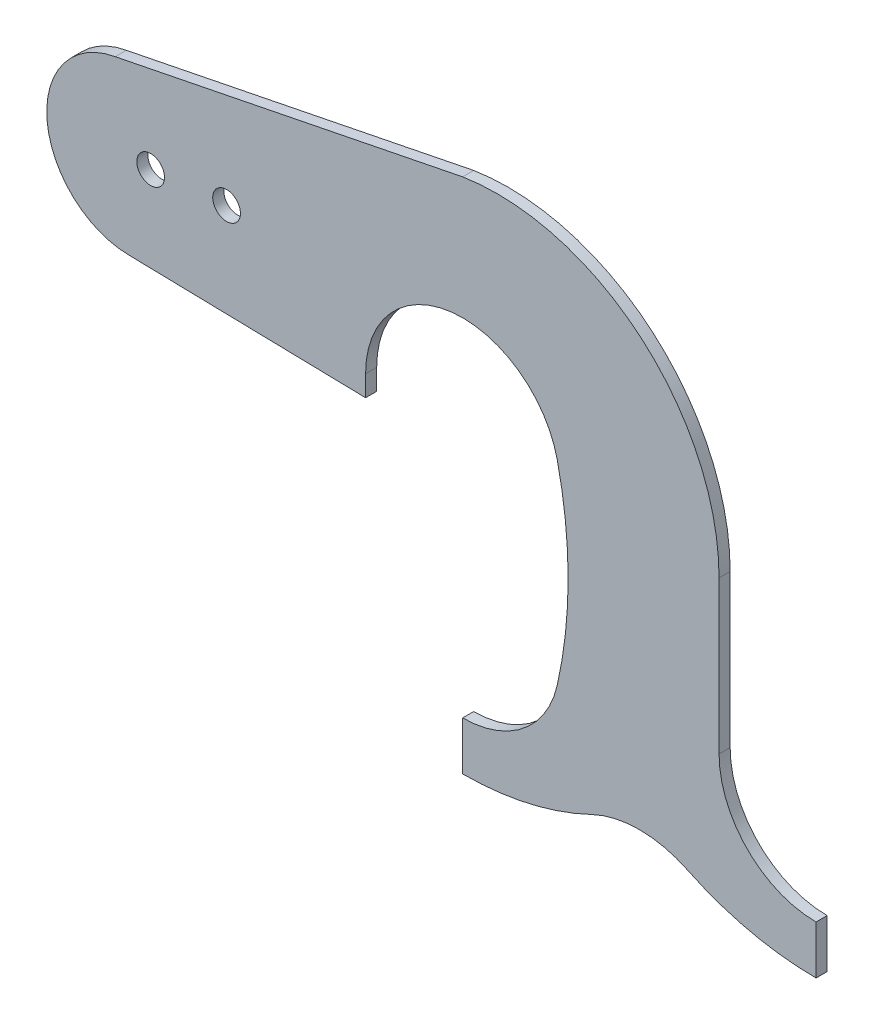
SolidWorks part; units mm, degrees
ref_plane "Front Plane" through (0, 0, 0) normal (0, 0, 1) x (1, 0, 0)
ref_plane "Top Plane" through (0, 0, 0) normal (0, 1, 0) x (1, 0, 0)
ref_plane "Right Plane" through (0, 0, 0) normal (1, 0, 0) x (0, 0, -1)
sketch "Sketch1" plane through (0, 0, 0) normal (0, 0, 1) x (1, 0, 0)
  line L0 (-87.5, 0) -> (1015.6132, 0) construction
  line L1 (0, 547.0247) -> (0, -524.0348) construction
  line L2 (0, -137.5) -> (1015.6132, -137.5) construction
  line L3 (231.25, 0) -> (231.25, -137.5)
  line L4 (318.75, 0) -> (318.75, -536.2059) construction
  line L5 (318.75, -225) -> (318.75, -268.75)
  line L6 (0, -225) -> (0, -268.75)
  line L7 (-87.5, 0) -> (-87.5, -18.75)
  line L8 (-9.6845, 86.9624) -> (-300, 60.9275) construction
  line L9 (-313.2695, 134.7443) -> (0, 197.5435)
  line L10 (-300, -14.0725) -> (-87.5, -18.75)
  arc A0 (-87.5, 0) -> (85.3562, 19.25) centre (0, 0) cw
  arc A1 (0, -225) -> (85.3562, -156.75) centre (0, -137.5) ccw
  arc A2 (85.3562, 19.25) -> (85.3562, -156.75) centre (-304.8437, -68.75) cw
  arc A3 (231.25, 0) -> (0, 197.5435) centre (31.25, 0) ccw
  arc A4 (231.25, -137.5) -> (318.75, -225) centre (318.75, -137.5) ccw
  arc A5 (318.75, -268.75) -> (202.5953, -242.3523) centre (318.75, 0) cw
  arc A6 (0, -268.75) -> (116.1547, -242.3523) centre (0, 0) ccw
  arc A7 (116.1547, -242.3523) -> (202.5953, -242.3523) centre (159.375, -332.53) cw
  arc A8 (-313.2695, 134.7443) -> (-300, -14.0725) centre (-300, 60.9275) ccw
  circle A9 centre (-281.3249, 62.6022) radius 12.5
  circle A10 centre (-212.8497, 68.7429) radius 12.5
  dimension "D1" = 87.5
  dimension "D2" = 87.5
  dimension "D4" = 400
  dimension "D5" = 200
  dimension "D7" = 87.5
  dimension "D9" = 268.75
  dimension "D10" = 100
  dimension "D13" = 75
  dimension "D16" = 25
  dimension "D3" = 137.5
  dimension "D6" = 31.25
  dimension "D8" = 43.75
  dimension "D11" = 18.75
  dimension "D12" = 300
  dimension "D14" = 18.75
  dimension "D15" = 68.75
extrude "Boss-Extrude1" add sketch "Sketch1" along normal blind 10
